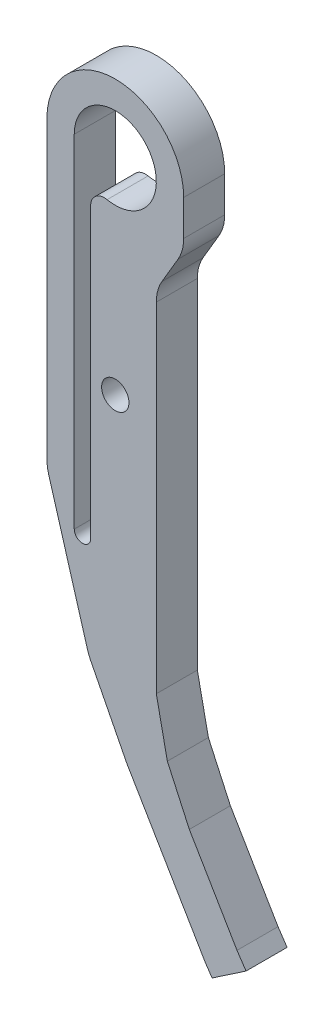
SolidWorks part; units mm, degrees
ref_plane "前视基准面" through (0, 0, 0) normal (0, 0, 1) x (1, 0, 0)
ref_plane "上视基准面" through (0, 0, 0) normal (0, 1, 0) x (1, 0, 0)
ref_plane "右视基准面" through (0, 0, 0) normal (1, 0, 0) x (0, 0, -1)
sketch "草图1" plane through (0, 0, 0) normal (0, 0, 1) x (1, 0, 0)
  line L0 (-3, -25) -> (-3, 0)
  line L1 (-1.8, -3.9192) -> (-1.8, -25)
  line L2 (5, 0) -> (5, -2.5985)
  line L3 (4.5848, -4.1213) -> (3.4152, -6.1066)
  line L4 (3, -7.6294) -> (3, -32.4273)
  line L5 (3, -32.4273) -> (3.8071, -36.2923)
  line L6 (3.8071, -36.2923) -> (5.4151, -39.8076)
  line L7 (5.4151, -39.8076) -> (8.8998, -45.723)
  line L8 (8.8998, -45.723) -> (9.5626, -46.7026)
  line L9 (7.078, -48.3838) -> (6.5657, -47.6268)
  line L10 (6.5657, -47.6268) -> (0.8801, -37.975)
  line L11 (0.7913, -37.813) -> (-1.7941, -32.7328)
  line L12 (-5, -21.5351) -> (-5, 0)
  line L13 (9.5626, -46.7026) -> (7.078, -48.3838)
  line L14 (-2.0327, -32.1325) -> (-4.8579, -22.5222)
  circle A0 centre (0, -15) radius 1
  arc A1 (-0.6, -2.9394) -> (-3, 0) centre (0, 0) ccw
  arc A2 (-3, -25) -> (-1.8, -25) centre (-2.4, -25) ccw
  arc A3 (-0.6, -2.9394) -> (-1.8, -3.9192) centre (-0.8, -3.9192) ccw
  arc A4 (4.5848, -4.1213) -> (5, -2.5985) centre (2, -2.5985) ccw
  arc A5 (3.4152, -6.1066) -> (3, -7.6294) centre (6, -7.6294) ccw
  arc A6 (0.7913, -37.813) -> (0.8801, -37.975) centre (3.4649, -36.4523) ccw
  arc A7 (-2.0327, -32.1325) -> (-1.7941, -32.7328) centre (1.3252, -31.1454) ccw
  arc A8 (5, 0) -> (-5, 0) centre (0, 0) ccw
  arc A9 (-5, -21.5351) -> (-4.8579, -22.5222) centre (-1.5, -21.5351) ccw
extrude "凸台-拉伸1" add sketch "草图1" along normal blind 3
